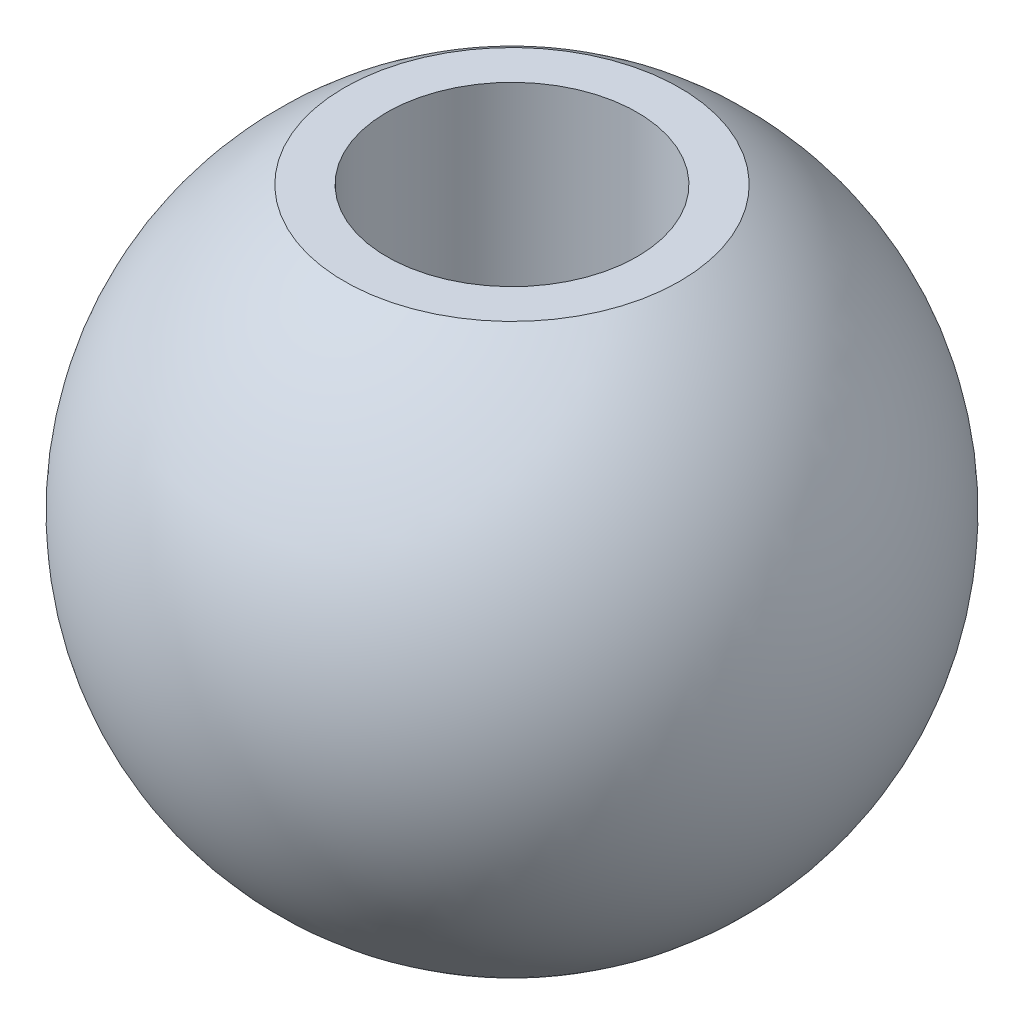
SolidWorks part; units mm, degrees
material "AISI 304"
ref_plane "Front Plane" through (0, 0, 0) normal (0, 0, 1) x (1, 0, 0)
ref_plane "Top Plane" through (0, 0, 0) normal (0, 1, 0) x (1, 0, 0)
ref_plane "Right Plane" through (0, 0, 0) normal (1, 0, 0) x (0, 0, -1)
sketch "Sketch1" plane through (0, 0, 0) normal (0, 0, 1) x (1, 0, 0)
  line L0 (0, 3.4) -> (0, -3.4) construction
  line L1 (2.0106, 3.4) -> (1.5, 3.4)
  line L2 (1.5, 3.4) -> (1.5, -3.4)
  line L3 (1.5, -3.4) -> (2.0106, -3.4)
  arc A0 (2.0106, 3.4) -> (2.0106, -3.4) centre (0, 0) cw
  point P3 (0, 0)
  dimension "D2" = 3.95
  dimension "D1" = 6.8
  dimension "D3" = 1.5
revolve "Revolve1" add sketch "Sketch1" angle 360 about L0
sketch "Sketch2" plane through (0, 0, 0) normal (0, 1, 0) x (1, 0, 0)
  point P0 (0, 0)
